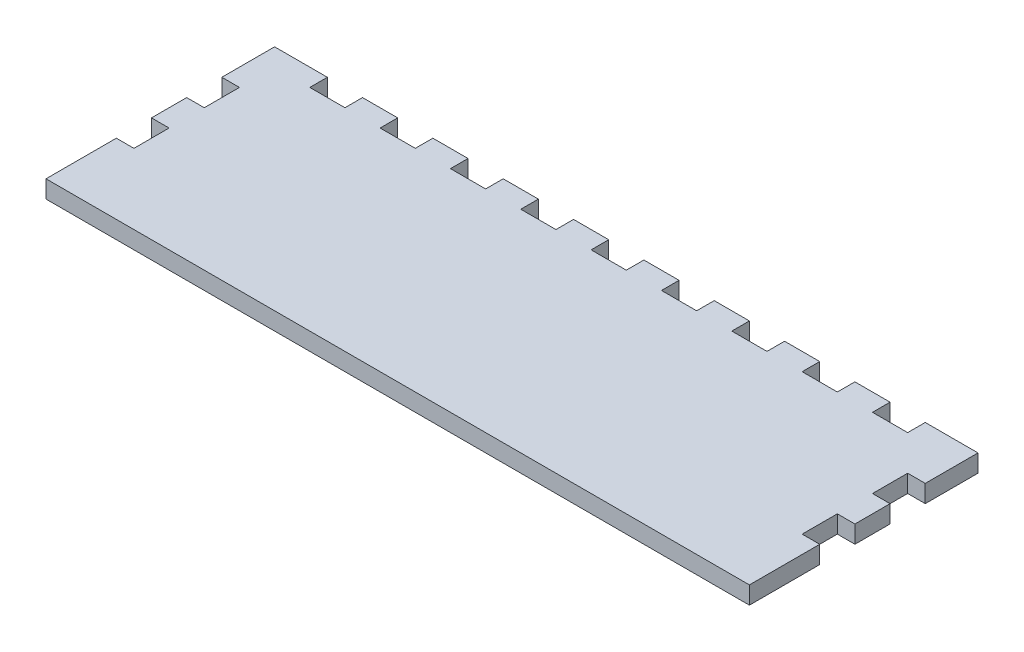
SolidWorks part; units mm, degrees
ref_plane "Front Plane" through (0, 0, 0) normal (1, 0, 0) x (0, 1, 0)
ref_plane "Top Plane" through (0, 0, 0) normal (0, 0, 1) x (0, 1, 0)
ref_plane "Right Plane" through (0, 0, 0) normal (0, 1, 0) x (-1, 0, 0)
sketch "Sketch3" plane through (0, 0, 0) normal (0, 1, 0) x (-1, 0, 0)
  line L1 (0, 0) -> (254, 0)
  line L2 (0, 0) -> (0, 82.55)
  line L3 (0, 82.55) -> (254, 82.55)
  line L4 (254, 0) -> (254, 82.55)
  dimension "D1" = 254
  dimension "D2" = 82.55
extrude "Boss-Extrude2" add sketch "Sketch3" along normal blind 6.35
sketch "Sketch4" plane through (0, 6.35, 0) normal (0, 1, 0) x (-1, 0, 0)
  line L0 (254, 0) -> (254, 82.55) construction
  line L5 (0, 82.55) -> (0, 0) construction
  line L10 (0, 0) -> (254, 0) construction
  line L11 (0, 19.05) -> (6.35, 19.05)
  line L12 (0, 19.05) -> (0, 31.75)
  line L13 (0, 31.75) -> (6.35, 31.75)
  line L14 (6.35, 19.05) -> (6.35, 31.75)
  line L15 (0, 44.45) -> (6.35, 44.45)
  line L16 (0, 44.45) -> (0, 57.15)
  line L17 (0, 57.15) -> (6.35, 57.15)
  line L18 (6.35, 44.45) -> (6.35, 57.15)
  line L23 (247.65, 19.05) -> (254, 19.05)
  line L24 (247.65, 19.05) -> (247.65, 31.75)
  line L25 (247.65, 31.75) -> (254, 31.75)
  line L26 (254, 19.05) -> (254, 31.75)
  line L27 (247.65, 44.45) -> (254, 44.45)
  line L28 (247.65, 44.45) -> (247.65, 57.15)
  line L29 (247.65, 57.15) -> (254, 57.15)
  line L30 (254, 44.45) -> (254, 57.15)
  line L31 (44.45, 0) -> (57.15, 0)
  line L32 (19.05, 0) -> (31.75, 0)
  line L33 (19.05, 0) -> (19.05, 6.35)
  line L34 (19.05, 6.35) -> (31.75, 6.35)
  line L35 (31.75, 0) -> (31.75, 6.35)
  line L36 (44.45, 0) -> (44.45, 6.35)
  line L37 (44.45, 6.35) -> (57.15, 6.35)
  line L38 (57.15, 0) -> (57.15, 6.35)
  line L39 (69.85, 0) -> (82.55, 0)
  line L40 (69.85, 0) -> (69.85, 6.35)
  line L41 (69.85, 6.35) -> (82.55, 6.35)
  line L42 (82.55, 0) -> (82.55, 6.35)
  line L43 (95.25, 0) -> (107.95, 0)
  line L44 (95.25, 0) -> (95.25, 6.35)
  line L45 (95.25, 6.35) -> (107.95, 6.35)
  line L46 (107.95, 0) -> (107.95, 6.35)
  line L47 (120.65, 0) -> (133.35, 0)
  line L48 (120.65, 0) -> (120.65, 6.35)
  line L49 (120.65, 6.35) -> (133.35, 6.35)
  line L50 (133.35, 0) -> (133.35, 6.35)
  line L51 (171.45, 0) -> (184.15, 0)
  line L52 (146.05, 0) -> (158.75, 0)
  line L53 (146.05, 0) -> (146.05, 6.35)
  line L54 (146.05, 6.35) -> (158.75, 6.35)
  line L55 (158.75, 0) -> (158.75, 6.35)
  line L56 (171.45, 0) -> (171.45, 6.35)
  line L57 (171.45, 6.35) -> (184.15, 6.35)
  line L58 (184.15, 0) -> (184.15, 6.35)
  line L59 (196.85, 0) -> (209.55, 0)
  line L60 (196.85, 0) -> (196.85, 6.35)
  line L61 (196.85, 6.35) -> (209.55, 6.35)
  line L62 (209.55, 0) -> (209.55, 6.35)
  line L63 (222.25, 0) -> (234.95, 0)
  line L64 (222.25, 0) -> (222.25, 6.35)
  line L65 (222.25, 6.35) -> (234.95, 6.35)
  line L66 (234.95, 0) -> (234.95, 6.35)
  point P17 (0, 50.8)
  point P43 (69.85, 3.175)
  dimension "D5" = 12.7
  dimension "D6" = 6.35
  dimension "D8" = 0
  dimension "D9" = 12.7
  dimension "D10" = 6.35
  dimension "D11" = 0
  dimension "D12" = 12.7
  dimension "D15" = 12.7
  dimension "D16" = 6.35
  dimension "D18" = 12.7
  dimension "D19" = 6.35
  dimension "D20" = 12.7
  dimension "D22" = 0
  dimension "D24" = 12.7
  dimension "D25" = 6.35
  dimension "D27" = 12.7
  dimension "D28" = 6.35
  dimension "D29" = 0
  dimension "D30" = 12.7
  dimension "D31" = 12.7
  dimension "D32" = 6.35
  dimension "D33" = 12.7
  dimension "D34" = 0
  dimension "D35" = 12.7
  dimension "D36" = 6.35
  dimension "D37" = 0
  dimension "D38" = 12.7
  dimension "D39" = 12.7
  dimension "D40" = 6.35
  dimension "D41" = 0
  dimension "D42" = 12.7
  dimension "D43" = 12.7
  dimension "D44" = 12.7
  dimension "D45" = 6.35
  dimension "D46" = 12.7
  dimension "D47" = 6.35
  dimension "D48" = 12.7
  dimension "D49" = 0
  dimension "D50" = 12.7
  dimension "D51" = 6.35
  dimension "D52" = 0
  dimension "D53" = 12.7
  dimension "D54" = 12.7
  dimension "D56" = 0
  dimension "D57" = 12.7
extrude "Cut-Extrude2" cut sketch "Sketch4" against normal blind 6.35
